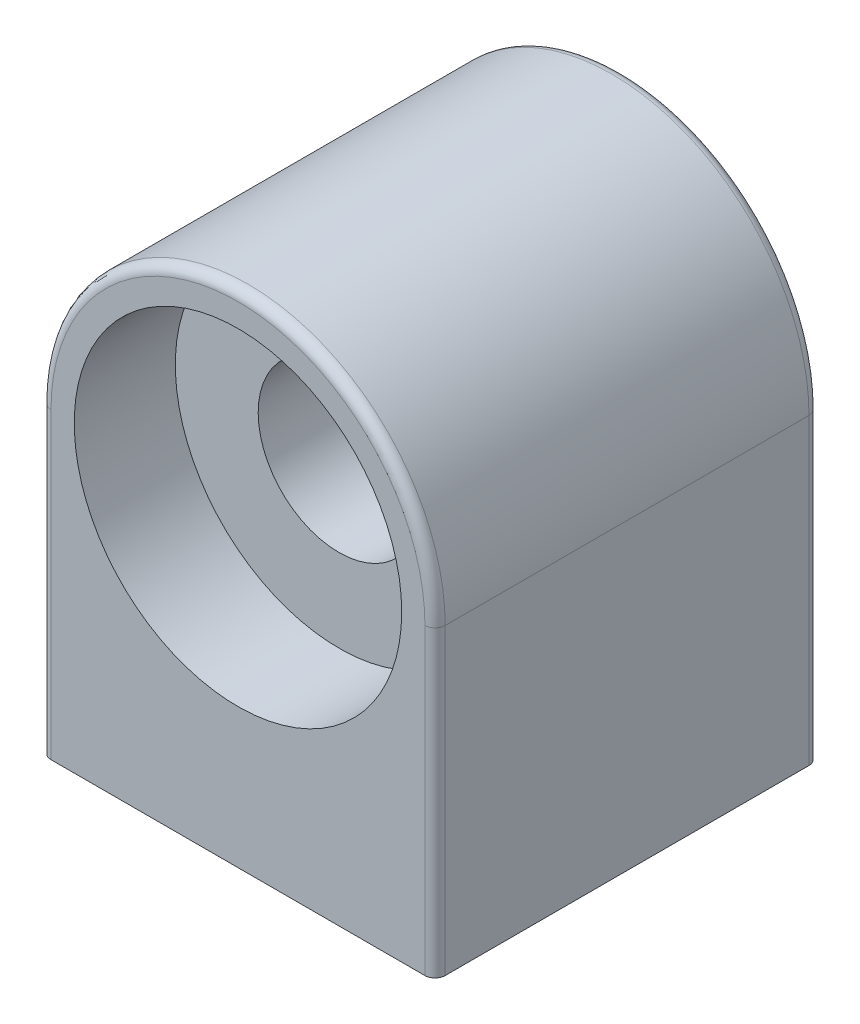
SolidWorks part; units mm, degrees
ref_plane "Front Plane" through (0, 0, 0) normal (0, 0, 1) x (1, 0, 0)
ref_plane "Top Plane" through (0, 0, 0) normal (0, 1, 0) x (1, 0, 0)
ref_plane "Right Plane" through (0, 0, 0) normal (1, 0, 0) x (0, 0, -1)
sketch "Sketch3" plane through (0, 0, 0) normal (0, 0, 1) x (1, 0, 0)
  line L0 (9.75, 0) -> (-9.75, 0) construction
  line L1 (9.75, 0) -> (9.75, -15)
  line L2 (-9.75, 0) -> (-9.75, -15)
  line L3 (9.75, -15) -> (-9.75, -15)
  arc A0 (9.75, 0) -> (-9.75, 0) centre (0, 0) ccw
  dimension "D1" = 19.5
  dimension "D2" = 15
extrude "Boss-Extrude2" add sketch "Sketch3" along normal mid plane 19
sketch "Sketch4" plane through (0, 0, -9.5) normal (0, 0, -1) x (-1, 0, 0)
  circle A0 centre (0, 0) radius 4
  dimension "D1" = 8
extrude "Cut-Extrude1" cut sketch "Sketch4" against normal through all
sketch "Sketch9" plane through (0, 0, -9.5) normal (0, 0, -1) x (-1, 0, 0)
  circle A0 centre (0, 0) radius 8.1
  dimension "D1" = 16.2
extrude "Cut-Extrude3" cut sketch "Sketch9" against normal blind 5
sketch "Sketch10" plane through (0, 0, 9.5) normal (0, 0, 1) x (1, 0, 0)
  circle A0 centre (0, 0) radius 8.1
  dimension "D1" = 16.2
extrude "Cut-Extrude4" cut sketch "Sketch10" against normal blind 5
sketch "Sketch12" plane through (0, -15, 0) normal (0, -1, 0) x (1, 0, 0)
  circle A0 centre (0, 0) radius 2.55
  dimension "D1" = 5.1
extrude "Cut-Extrude6" cut sketch "Sketch12" against normal blind 8
fillet "Fillet1" radius 0.5 6 edges at (9.75, -7.5, -9.5) (0, 9.75, -9.5) (9.75, -7.5, 9.5) (0, 9.75, 9.5) (-9.75, -7.5, -9.5) (-9.75, -7.5, 9.5)
